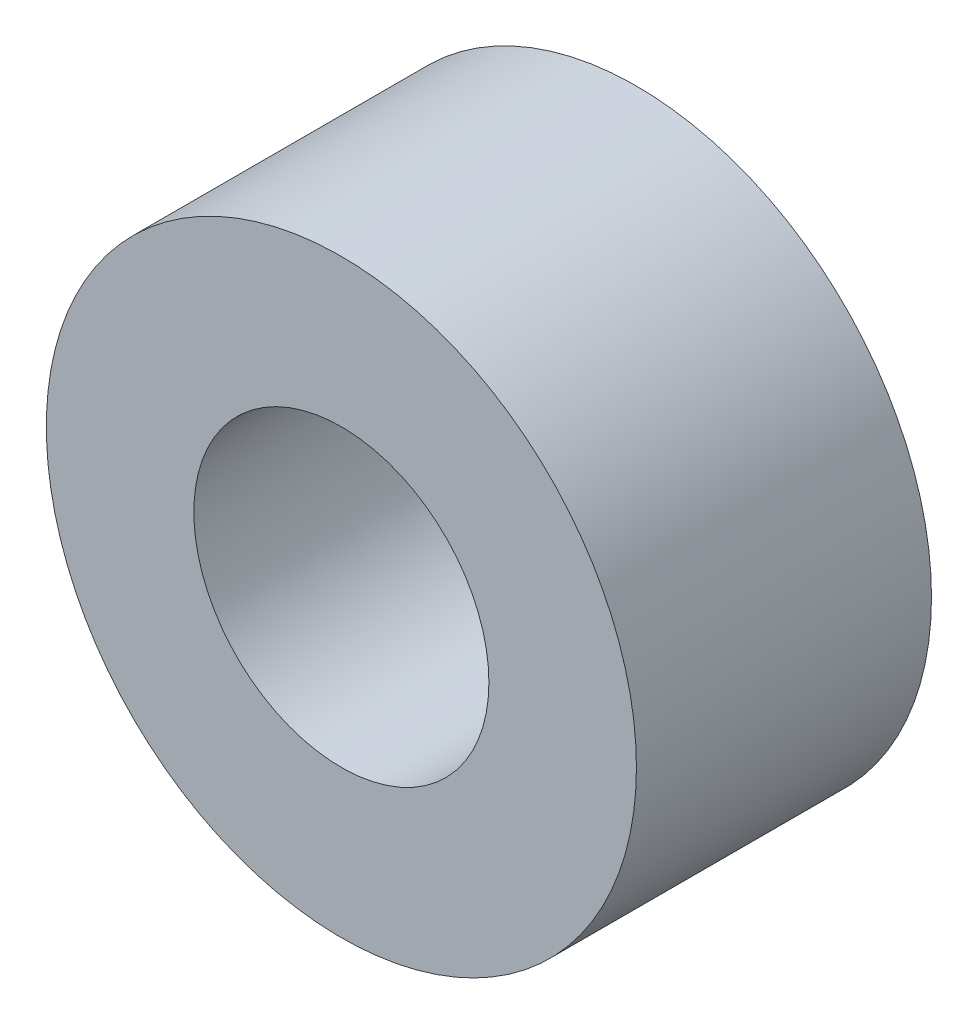
SolidWorks part; units mm, degrees
ref_plane "Front Plane" through (0, 0, 0) normal (0, 0, 1) x (1, 0, 0)
ref_plane "Top Plane" through (0, 0, 0) normal (0, 1, 0) x (1, 0, 0)
ref_plane "Right Plane" through (0, 0, 0) normal (1, 0, 0) x (0, 0, -1)
sketch "Sketch1" plane through (0, 0, 0) normal (0, 0, 1) x (1, 0, 0)
  circle A0 centre (0, 0) radius 5
  circle A1 centre (0, 0) radius 10
  dimension "D1" = 10
  dimension "D2" = 20
extrude "Boss-Extrude1" add sketch "Sketch1" along normal blind 10
